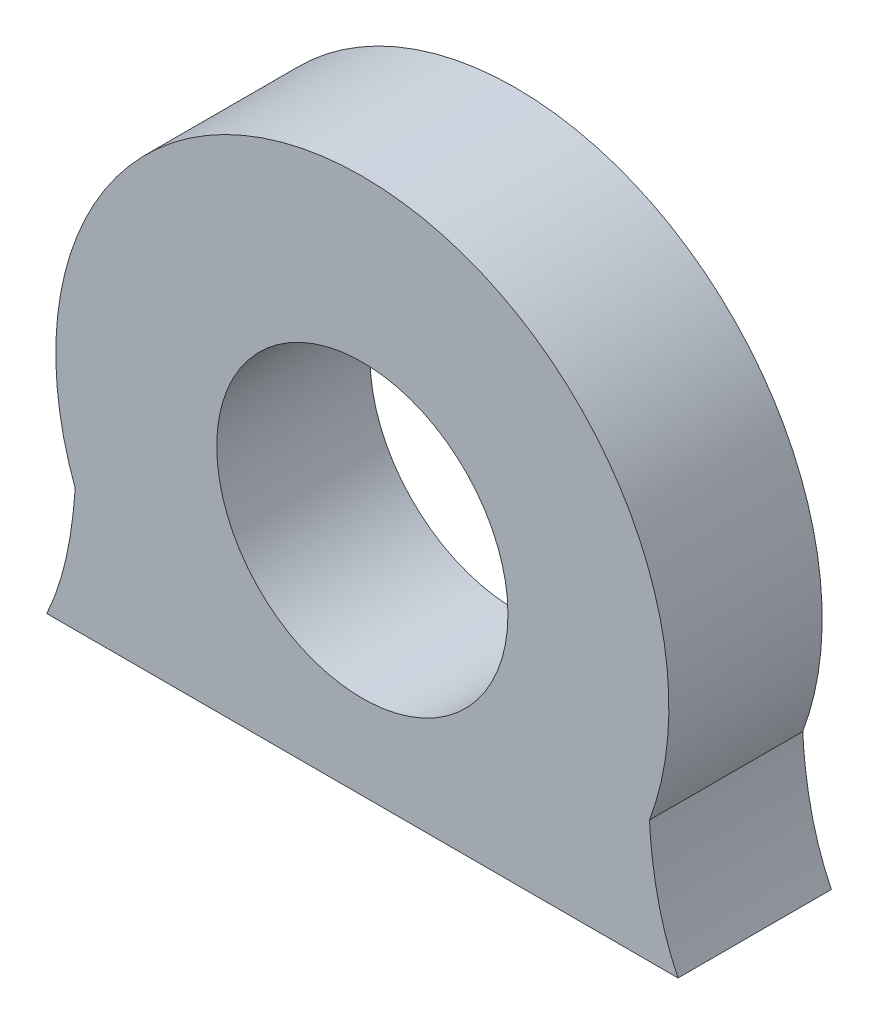
SolidWorks part; units mm, degrees
ref_plane "Front Plane" through (0, 0, 0) normal (0, 0, 1) x (1, 0, 0)
ref_plane "Top Plane" through (0, 0, 0) normal (0, 1, 0) x (1, 0, 0)
ref_plane "Right Plane" through (0, 0, 0) normal (1, 0, 0) x (0, 0, -1)
sketch "Sketch1" plane through (0, 0, 0) normal (0, 0, 1) x (1, 0, 0)
  line L0 (-25, -20) -> (25, -20)
  circle A0 centre (0, 0) radius 9.5
  arc A1 (18.7325, -7.0067) -> (-18.7325, -7.0067) centre (0, 0) ccw
  spline S0 degree 2 poles (-18.7325, -7.0067) (-19.3934, -16.6368) (-25, -20) knots 0 0 0 0.631911 0.631911 0.631911
  spline S1 degree 2 poles (18.7325, -7.0067) (19.2136, -16.2567) (25, -20) knots 0 0 0 0.763362 0.763362 0.763362
  point P7 (0, -20)
extrude "Boss-Extrude1" add sketch "Sketch1" along normal blind 10
sketch "Sketch2" plane through (0, 0, 10) normal (0, 0, 1) x (1, 0, 0)
  line L1 (-25, -20) -> (25.0481, -20)
  line L2 (-25, -20) -> (-25, -15)
  line L3 (-25, -15) -> (25.0481, -15)
  line L4 (25.0481, -20) -> (25.0481, -15)
  dimension "D1" = 5
extrude "Cut-Extrude1" cut sketch "Sketch2" against normal blind 10
